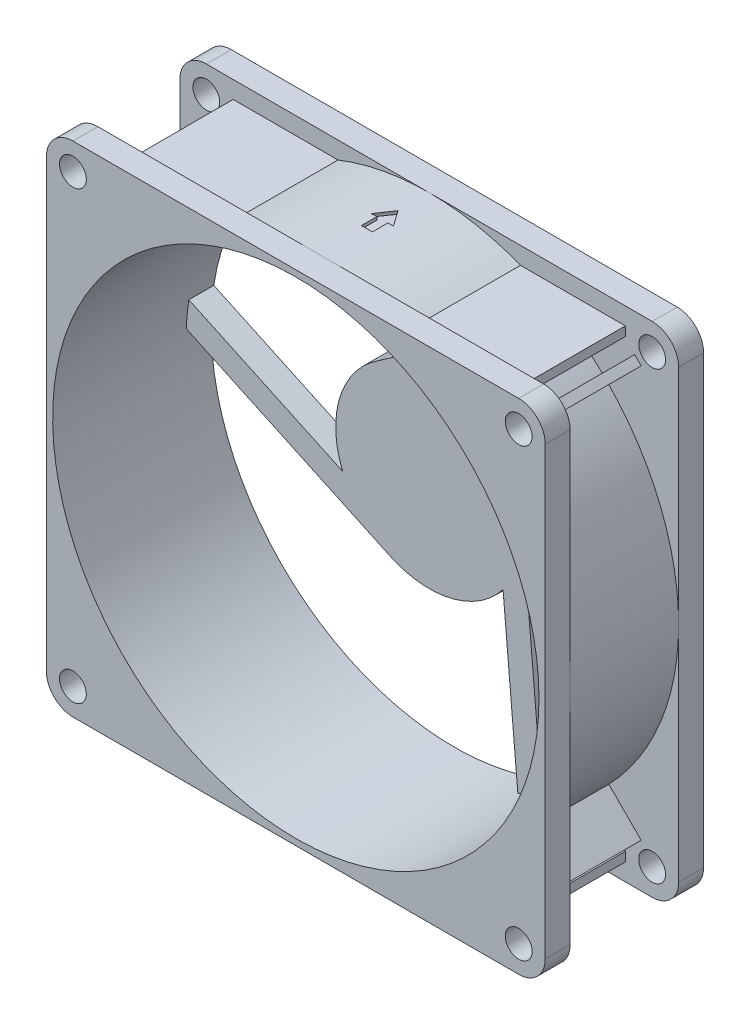
SolidWorks part; units mm, degrees
material "PW100:Mi:0:3:C1:0:1:2:Re:26:"
ref_plane "Front" through (0, 0, 0) normal (0, 0, 1) x (1, 0, 0)
ref_plane "Top" through (0, 0, 0) normal (0, 1, 0) x (1, 0, 0)
ref_plane "Right" through (0, 0, 0) normal (1, 0, 0) x (0, 0, -1)
sketch "Support-Front" plane through (0, 0, 0) normal (0, 0, 1) x (1, 0, 0)
  line L0 (-40, 0) -> (40, 0) construction
  line L1 (0, 40) -> (0, -40) construction
  line L2 (40, -35.75) -> (40, 35.75)
  line L3 (-40, -35.75) -> (-40, 35.75)
  line L4 (35.75, 40) -> (-35.75, 40)
  line L5 (35.75, -40) -> (-35.75, -40)
  line L6 (0, 40) -> (0, 54.8081) construction
  arc A0 (40, 35.75) -> (35.75, 40) centre (35.75, 35.75) ccw
  arc A1 (-40, 35.75) -> (-35.75, 40) centre (-35.75, 35.75) cw
  arc A2 (-40, -35.75) -> (-35.75, -40) centre (-35.75, -35.75) ccw
  arc A3 (40, -35.75) -> (35.75, -40) centre (35.75, -35.75) cw
  circle A4 centre (35.75, 35.75) radius 2.15
  circle A5 centre (-35.75, 35.75) radius 2.15
  circle A6 centre (-35.75, -35.75) radius 2.15
  circle A7 centre (35.75, -35.75) radius 2.15
  circle A8 centre (0, 0) radius 39
  circle A9 centre (0, 0) radius 15
  circle A10 centre (0, 0) radius 40
  circle A11 centre (0, 0) radius 54.8081 construction
  dimension "Diam-Fixing-Hole" = 4.3
  dimension "Diam-Fan-Hole" = 78
  dimension "Diam-Fixing-Plate-Fan" = 30
  dimension "Dist-Fixing-Hole" = 71.5
  dimension "Width" = 80
sketch "Support-Right" plane through (0, 0, 0) normal (1, 0, 0) x (0, 0, -1)
  line L0 (-25.4, 0) -> (0, 0) construction
  line L1 (-12.7, 40) -> (-12.7, -40) construction
  line L2 (-4, 40) -> (-4, -40)
  line L3 (-25.4, 40) -> (0, 40)
  line L4 (-25.4, 40) -> (-25.4, -40)
  line L5 (-25.4, -40) -> (0, -40)
  line L6 (0, 40) -> (0, -40)
  line L7 (-21.4, 40) -> (-21.4, -40)
  line L8 (-12.7, 40) -> (-12.7, 42) construction
  line L9 (0, 0) -> (-2, 0) construction
  line L10 (-2, 0) -> (-4, 0) construction
  dimension "Thickness" = 25.4
  dimension "Thickness-Flange" = 4
sketch "Support-Front-Reinforcment-Place" plane through (0, 0, 0) normal (0, 0, 1) x (1, 0, 0)
  line L0 (0, 40) -> (0, 0) construction
  line L1 (0, 39) -> (0, 40) construction
  line L2 (12.612, 40) -> (13.1937, 36.7005)
  line L3 (35.75, 40) -> (-35.75, 40) construction
  line L4 (-12.612, 40) -> (-13.1937, 36.7005)
  line L5 (12.612, 40) -> (0, 0) construction
  line L6 (-12.612, 40) -> (0, 0) construction
  line L7 (12.612, 40) -> (-12.612, 40)
  circle A3 centre (0, 0) radius 39 construction
  arc A4 (13.1937, 36.7005) -> (-13.1937, 36.7005) centre (0, 0) ccw
  point P10 (0, 39.5)
  dimension "D1" = 20
  dimension "D2" = 35
sketch "Support-Front-Reinforcment-Strip" plane through (0, 0, 0) normal (0, 0, 1) x (1, 0, 0)
  line L0 (14.6325, 37.2275) -> (31.45, 37.2275)
  line L1 (28.8018, 27.7571) -> (33.992, 32.9472)
  line L2 (35.75, 35.75) -> (0, 0) construction
  line L3 (33.992, 32.9472) -> (32.9472, 33.992)
  line L4 (31.45, 37.2275) -> (31.45, 35.75)
  line L5 (32.9472, 33.992) -> (27.7571, 28.8018)
  line L6 (31.45, 35.75) -> (17.9426, 35.75)
  line L7 (35.75, 40) -> (-35.75, 40) construction
  line L8 (35.75, 35.75) -> (33.6, 35.75) construction
  line L13 (33.4696, 33.4696) -> (28.2843, 28.2843) construction
  line L14 (35.75, 35.75) -> (34.9899, 34.9899) construction
  line L15 (34.9899, 34.9899) -> (34.2297, 34.2297) construction
  line L16 (34.2297, 34.2297) -> (33.4696, 33.4696) construction
  line L17 (33.6, 35.75) -> (31.45, 35.75) construction
  line L18 (35.75, 35.75) -> (28.8018, 27.7571) construction
  line L19 (37.2275, 14.6325) -> (37.2275, 31.45)
  line L20 (37.2275, 31.45) -> (35.75, 31.45)
  line L21 (35.75, 31.45) -> (35.75, 17.9426)
  line L22 (0, 40) -> (0, -40) construction
  line L23 (-40, 0) -> (40, 0) construction
  line L24 (-40, 0) -> (40, 0) construction
  line L25 (0, 40) -> (0, -40) construction
  line L26 (-37.2275, 14.6325) -> (-37.2275, 31.45)
  line L27 (-35.75, 31.45) -> (-35.75, 17.9426)
  line L28 (-37.2275, 31.45) -> (-35.75, 31.45)
  line L29 (-14.6325, 37.2275) -> (-31.45, 37.2275)
  line L30 (-31.45, 37.2275) -> (-31.45, 35.75)
  line L31 (-31.45, 35.75) -> (-17.9426, 35.75)
  line L32 (-37.2275, -14.6325) -> (-37.2275, -31.45)
  line L33 (-35.75, -31.45) -> (-35.75, -17.9426)
  line L34 (-37.2275, -31.45) -> (-35.75, -31.45)
  line L35 (-31.45, -35.75) -> (-17.9426, -35.75)
  line L36 (-31.45, -37.2275) -> (-31.45, -35.75)
  line L37 (-14.6325, -37.2275) -> (-31.45, -37.2275)
  line L38 (14.6325, -37.2275) -> (31.45, -37.2275)
  line L39 (31.45, -37.2275) -> (31.45, -35.75)
  line L40 (31.45, -35.75) -> (17.9426, -35.75)
  line L41 (37.2275, -31.45) -> (35.75, -31.45)
  line L42 (35.75, -31.45) -> (35.75, -17.9426)
  line L43 (37.2275, -14.6325) -> (37.2275, -31.45)
  arc A0 (17.9426, 35.75) -> (14.6325, 37.2275) centre (0, 0) ccw
  circle A1 centre (35.75, 35.75) radius 2.15 construction
  circle A3 centre (0, 0) radius 40 construction
  arc A4 (35.75, 17.9426) -> (37.2275, 14.6325) centre (0, 0) cw
  arc A5 (-35.75, 17.9426) -> (-37.2275, 14.6325) centre (0, 0) ccw
  arc A6 (28.8018, 27.7571) -> (27.7571, 28.8018) centre (0, 0) ccw
  arc A7 (-17.9426, 35.75) -> (-14.6325, 37.2275) centre (0, 0) cw
  arc A8 (-35.75, -17.9426) -> (-37.2275, -14.6325) centre (0, 0) cw
  arc A9 (-17.9426, -35.75) -> (-14.6325, -37.2275) centre (0, 0) ccw
  arc A10 (17.9426, -35.75) -> (14.6325, -37.2275) centre (0, 0) cw
  arc A11 (35.75, -17.9426) -> (37.2275, -14.6325) centre (0, 0) ccw
  dimension "D1" = 4
sketch "Support-Front-Bone" plane through (0, 0, 0) normal (0, 0, 1) x (1, 0, 0)
  line L0 (13.5946, -6.3393) -> (16.1459, -35.5008) construction
  line L1 (11.8383, -9.2117) -> (14.2099, -36.3191)
  line L2 (14.9801, 0.7714) -> (18.0713, -34.5605)
  line L3 (0, 0) -> (0, 40) construction
  line L4 (35.75, 40) -> (-35.75, 40) construction
  line L6 (0, 0) -> (13.5946, -6.3393) construction
  circle A0 centre (0, 0) radius 39 construction
  circle A1 centre (0, 0) radius 15 construction
  arc A2 (11.8383, -9.2117) -> (14.9801, 0.7714) centre (0, 0) ccw
  arc A3 (14.2099, -36.3191) -> (18.0713, -34.5605) centre (0, 0) ccw
  dimension "Angle-Bone" = 175
  dimension "Angle-Place-Bone" = 115
  dimension "Thickness-Flange" = 4
sketch "Support-Air-Exhaust" plane through (0, 0, 0) normal (0, 1, 0) x (1, 0, 0)
  line L0 (0, 0) -> (0, -9) construction
  line L1 (0, -9) -> (0, -11.5) construction
  line L2 (0, -11.5) -> (0, -14) construction
  line L3 (0, -14) -> (0, -9) construction
  line L4 (0.8816, -14) -> (-0.8816, -14)
  line L5 (-0.8816, -14) -> (-0.8816, -11.5)
  line L6 (-0.8816, -11.5) -> (-1.7505, -11.5)
  line L7 (-1.7505, -11.5) -> (0, -9)
  line L8 (0, -9) -> (-0.8816, -14) construction
  line L9 (1.7505, -11.5) -> (0, -9)
  line L10 (0.8816, -11.5) -> (1.7505, -11.5)
  line L11 (0.8816, -14) -> (0.8816, -11.5)
  dimension "D1" = 5
  dimension "D2" = 9
  dimension "D3" = 10
  dimension "D4" = 35
ref_plane "Plane1" through (0, 0, 25.4) normal (0, 0, 1) x (1, 0, 0)
ref_plane "Plane2" through (0, 39.5, 0) normal (0, 1, 0) x (-1, 0, 0)
sketch "Sketch-Body" plane through (0, 0, 0) normal (0, 0, 1) x (1, 0, 0)
  line L4 (-35.75, -40) -> (35.75, -40)
  line L5 (-40, 35.75) -> (-40, -35.75)
  line L6 (35.75, 40) -> (-35.75, 40)
  line L7 (40, -35.75) -> (40, 35.75)
  line L8 (-35.75, -40) -> (35.75, -40)
  line L9 (-40, 35.75) -> (-40, -35.75)
  line L10 (35.75, 40) -> (-35.75, 40)
  line L11 (40, -35.75) -> (40, 35.75)
  circle A0 centre (0, 0) radius 39 construction
  circle A1 centre (0, 0) radius 39
  arc A4 (-40, -35.75) -> (-35.75, -40) centre (-35.75, -35.75) ccw
  arc A5 (-35.75, 40) -> (-40, 35.75) centre (-35.75, 35.75) ccw
  arc A6 (40, 35.75) -> (35.75, 40) centre (35.75, 35.75) ccw
  arc A7 (35.75, -40) -> (40, -35.75) centre (35.75, -35.75) ccw
  arc A8 (-40, -35.75) -> (-35.75, -40) centre (-35.75, -35.75) ccw
  arc A9 (-35.75, 40) -> (-40, 35.75) centre (-35.75, 35.75) ccw
  arc A10 (40, 35.75) -> (35.75, 40) centre (35.75, 35.75) ccw
  arc A11 (35.75, -40) -> (40, -35.75) centre (35.75, -35.75) ccw
  dimension "D1" = 0
extrude "Body" add sketch "Sketch-Body" along normal up to surface (25.4 mm away) up to plane "Plane1"
sketch "Sketch-Cut-Body" plane through (0, 0, 0) normal (1, 0, 0) x (0, 0, -1)
  line L0 (-25.4, 0) -> (0, 0) construction
  line L1 (-25.4, 0) -> (0, 0) construction
  line L2 (-25.4, 40) -> (0, 40) construction
  line L5 (-21.4, 40) -> (-21.4, 54.8081)
  line L6 (-21.4, 54.8081) -> (-4, 54.8081)
  line L7 (-21.4, 40) -> (-4, 40)
  line L9 (-4, 54.8081) -> (-4, 40)
  line L10 (-4, 40) -> (-4, -40) construction
  line L11 (-21.4, 40) -> (-21.4, -40) construction
revolve "Cut-Body" cut sketch "Sketch-Cut-Body" angle 360 about L1
sketch "Sketch-Reinforcment-Strip" plane through (0, 0, 0) normal (0, 0, 1) x (1, 0, 0)
  line L0 (28.8018, 27.7571) -> (33.992, 32.9472) construction
  line L2 (28.8018, 27.7571) -> (33.992, 32.9472)
  line L4 (32.9472, 33.992) -> (27.7571, 28.8018) construction
  line L5 (33.992, 32.9472) -> (32.9472, 33.992) construction
  line L6 (32.9472, 33.992) -> (27.7571, 28.8018)
  line L7 (33.992, 32.9472) -> (32.9472, 33.992)
  circle A1 centre (0, 0) radius 40 construction
  arc A3 (28.8018, 27.7571) -> (27.7571, 28.8018) centre (0, 0) ccw
extrude "Reinforcment-Strip" add sketch "Sketch-Reinforcment-Strip" along normal up to surface (25.4 mm away) up to plane "Plane1"
pattern_circular "CirPattern-Reinforcment-Strip" count 4 over 360 about axis through (0, 0, 0) along (0, 0, 1) of "Reinforcment-Strip"
sketch "Sketch-Fixing-Hole" plane through (0, 0, 0) normal (0, 0, 1) x (1, 0, 0)
  circle A0 centre (35.75, 35.75) radius 2.15 construction
  circle A1 centre (35.75, 35.75) radius 2.15
extrude "Fixing-Hole" cut sketch "Sketch-Fixing-Hole" along normal through all
pattern_circular "CirPattern-Fixing-Hole" count 4 over 360 about axis through (0, 0, 0) along (0, 0, 1) of "Fixing-Hole"
sketch "Sketch-Bone" plane through (0, 0, 0) normal (0, 0, 1) x (1, 0, 0)
  line L0 (14.9801, 0.7714) -> (18.0713, -34.5605) construction
  line L1 (11.8383, -9.2117) -> (14.2099, -36.3191) construction
  line L2 (14.9801, 0.7714) -> (18.0713, -34.5605)
  line L3 (11.8383, -9.2117) -> (14.2099, -36.3191)
  circle A0 centre (0, 0) radius 39 construction
  circle A1 centre (0, 0) radius 15 construction
  arc A2 (14.2099, -36.3191) -> (18.0713, -34.5605) centre (0, 0) ccw
  arc A3 (11.8383, -9.2117) -> (14.9801, 0.7714) centre (0, 0) ccw
extrude "Bone" add sketch "Sketch-Bone" along normal blind 4
pattern_circular "CirPattern-Bone" count 3 over 360 about axis through (0, 0, 0) along (0, 0, 1) of "Bone"
sketch "Sketch3" plane through (0, 0, 0) normal (0, 0, 1) x (1, 0, 0)
  line L0 (14.6325, 37.2275) -> (31.45, 37.2275) construction
  line L1 (31.45, 37.2275) -> (31.45, 35.75) construction
  line L2 (31.45, 35.75) -> (17.9426, 35.75) construction
  line L3 (14.6325, 37.2275) -> (31.45, 37.2275)
  line L4 (31.45, 37.2275) -> (31.45, 35.75)
  line L5 (31.45, 35.75) -> (17.9426, 35.75)
  line L6 (-31.45, 35.75) -> (-17.9426, 35.75) construction
  line L7 (-31.45, 37.2275) -> (-31.45, 35.75) construction
  line L8 (-14.6325, 37.2275) -> (-31.45, 37.2275) construction
  line L9 (-31.45, 35.75) -> (-17.9426, 35.75)
  line L10 (-31.45, 37.2275) -> (-31.45, 35.75)
  line L11 (-14.6325, 37.2275) -> (-31.45, 37.2275)
  line L12 (-31.45, -37.2275) -> (-31.45, -35.75) construction
  line L13 (-31.45, -35.75) -> (-17.9426, -35.75) construction
  line L14 (-14.6325, -37.2275) -> (-31.45, -37.2275) construction
  line L15 (-31.45, -37.2275) -> (-31.45, -35.75)
  line L16 (-31.45, -35.75) -> (-17.9426, -35.75)
  line L17 (-14.6325, -37.2275) -> (-31.45, -37.2275)
  line L18 (14.6325, -37.2275) -> (31.45, -37.2275) construction
  line L19 (31.45, -37.2275) -> (31.45, -35.75) construction
  line L20 (31.45, -35.75) -> (17.9426, -35.75) construction
  line L21 (14.6325, -37.2275) -> (31.45, -37.2275)
  line L22 (31.45, -37.2275) -> (31.45, -35.75)
  line L23 (31.45, -35.75) -> (17.9426, -35.75)
  arc A0 (17.9426, 35.75) -> (14.6325, 37.2275) centre (0, 0) ccw construction
  arc A1 (17.9426, 35.75) -> (14.6325, 37.2275) centre (0, 0) ccw
  arc A2 (-14.6325, 37.2275) -> (-17.9426, 35.75) centre (0, 0) ccw construction
  arc A3 (-14.6325, 37.2275) -> (-17.9426, 35.75) centre (0, 0) ccw
  arc A4 (-17.9426, -35.75) -> (-14.6325, -37.2275) centre (0, 0) ccw construction
  arc A5 (-17.9426, -35.75) -> (-14.6325, -37.2275) centre (0, 0) ccw
  arc A6 (14.6325, -37.2275) -> (17.9426, -35.75) centre (0, 0) ccw construction
  arc A7 (14.6325, -37.2275) -> (17.9426, -35.75) centre (0, 0) ccw
extrude "Reinforcment-Plates" add sketch "Sketch3" along normal up to surface (25.4 mm away) up to plane "Plane1"
sketch "Sketch-Fixing-Plate-Fan" plane through (0, 0, 0) normal (0, 0, 1) x (1, 0, 0)
  circle A0 centre (0, 0) radius 15 construction
  circle A1 centre (0, 0) radius 15
extrude "Fixing-Plate-Fan" add sketch "Sketch-Fixing-Plate-Fan" along normal blind 4
sketch "Sketch5" plane through (0, 39.5, 0) normal (0, 1, 0) x (-1, 0, 0)
  line L7 (0.8816, 14) -> (-0.8816, 14)
  line L8 (0.8816, 11.5) -> (0.8816, 14)
  line L9 (1.7505, 11.5) -> (0.8816, 11.5)
  line L10 (0, 9) -> (1.7505, 11.5)
  line L11 (-1.7505, 11.5) -> (0, 9)
  line L12 (-0.8816, 11.5) -> (-1.7505, 11.5)
  line L13 (-0.8816, 14) -> (-0.8816, 11.5)
  line L14 (0.8816, 14) -> (-0.8816, 14)
  line L15 (0.8816, 11.5) -> (0.8816, 14)
  line L16 (1.7505, 11.5) -> (0.8816, 11.5)
  line L17 (0, 9) -> (1.7505, 11.5)
  line L18 (-1.7505, 11.5) -> (0, 9)
  line L19 (-0.8816, 11.5) -> (-1.7505, 11.5)
  line L20 (-0.8816, 14) -> (-0.8816, 11.5)
  dimension "D1" = 0
extrude "Air-Exhaust" cut sketch "Sketch5" along normal through all
equation "\"Diam-Fan-Hole@Support-Front\" = \"Width@Support-Front\"-2"
